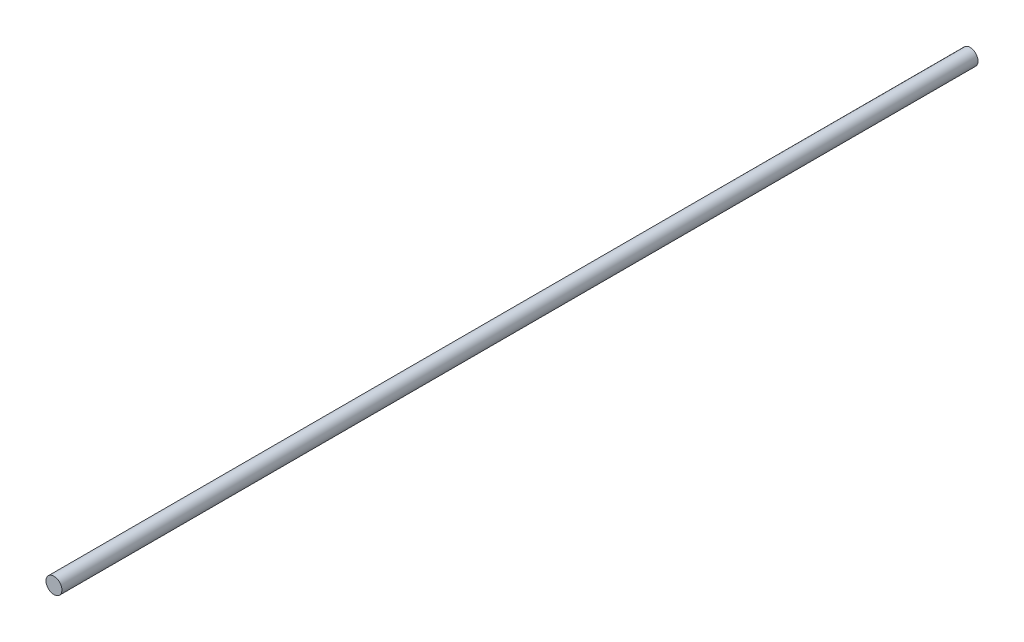
SolidWorks part; units mm, degrees
material "1.7244 (18CrMoS4)"
ref_plane "Přední rovina" through (0, 0, 0) normal (0, 0, 1) x (1, 0, 0)
ref_plane "Horní rovina" through (0, 0, 0) normal (0, 1, 0) x (1, 0, 0)
ref_plane "Pravá rovina" through (0, 0, 0) normal (1, 0, 0) x (0, 0, -1)
sketch "Skica1" plane through (0, 0, 0) normal (0, 0, 1) x (1, 0, 0)
  circle A0 centre (0, 0) radius 4
  dimension "D1" = 8
extrude "Přidat vysunutím1" add sketch "Skica1" along normal blind 460
